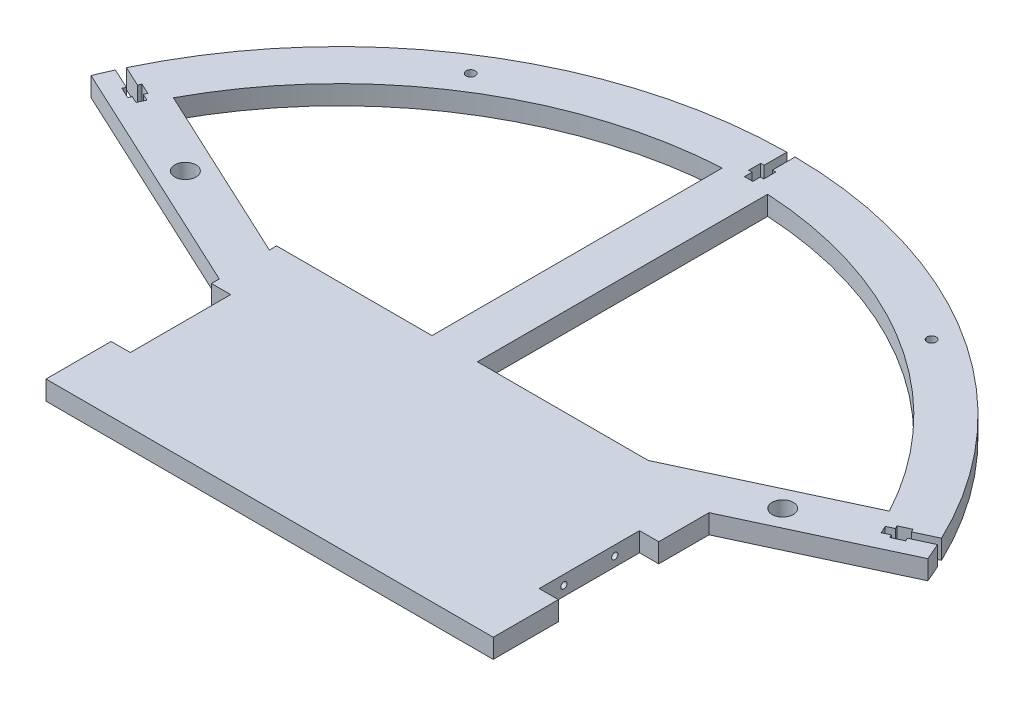
SolidWorks part; units mm, degrees
material "6061 Alloy"
ref_plane "Front Plane" through (0, 0, 0) normal (0, 0, 1) x (1, 0, 0)
ref_plane "Top Plane" through (0, 0, 0) normal (0, 1, 0) x (1, 0, 0)
ref_plane "Right Plane" through (0, 0, 0) normal (1, 0, 0) x (0, 0, -1)
sketch "Sketch1" plane through (0, 0, 0) normal (0, 1, 0) x (1, 0, 0)
  line L0 (0, 0) -> (0, 149.238) construction
  line L1 (0, 0) -> (135.2556, 63.0707) construction
  line L2 (0, 0) -> (-135.2556, 63.0707) construction
  line L3 (3.1696, 6.7973) -> (-132.0859, 69.868)
  line L4 (7.5, 0) -> (7.5, 149.238)
  line L5 (3.1696, -6.7973) -> (138.4252, 56.2734)
  line L6 (-3.1696, -6.7973) -> (-138.4252, 56.2734)
  line L7 (-7.5, 0) -> (-7.5, 149.238)
  line L8 (-3.1696, 6.7973) -> (132.0859, 69.868)
  line L10 (-58.85, -38.1) -> (88.95, -38.1)
  line L11 (-58.85, -38.1) -> (-58.85, 38.1)
  line L12 (-58.85, 38.1) -> (88.95, 38.1)
  line L13 (88.95, -38.1) -> (88.95, 38.1)
  line L14 (-58.85, -38.1) -> (88.95, 38.1) construction
  line L15 (-58.85, 38.1) -> (88.95, -38.1) construction
  circle A0 centre (0, 0) radius 150 construction
  circle A1 centre (0, 0) radius 149.238
  circle A2 centre (0, 0) radius 134.238
  circle A3 centre (0, 0) radius 14
  point P7 (0, 0)
  point P11 (0, 0)
  dimension "D1" = 150
  dimension "D2" = 0.762
  dimension "D3" = 15
  dimension "D10" = 28
  dimension "D4" = 65
  dimension "D5" = 65
  dimension "D8" = 147.8
  dimension "D9" = 76.2
  dimension "D11" = 58.85
  dimension "D12" = 38.1
  dimension "D6" = 7.5
  dimension "D7" = 7.5
extrude "Boss-Extrude1" add sketch "Sketch1" along normal mid plane 6.35
sketch "Sketch2" plane through (0, 0, 0) normal (0, 1, 0) x (1, 0, 0)
  line L0 (-1.375, 135.238) -> (-1.375, 149.238)
  line L1 (-1.375, 135.238) -> (1.375, 135.238)
  line L2 (-1.375, 149.238) -> (1.375, 149.238)
  line L3 (1.375, 135.238) -> (1.375, 149.238)
  line L4 (-1.375, 135.238) -> (1.375, 149.238) construction
  line L5 (-1.375, 149.238) -> (1.375, 135.238) construction
  line L6 (-2.5, 137.738) -> (-2.5, 141.738)
  line L7 (-2.5, 137.738) -> (2.5, 137.738)
  line L8 (-2.5, 141.738) -> (2.5, 141.738)
  line L9 (2.5, 137.738) -> (2.5, 141.738)
  line L10 (-2.5, 137.738) -> (2.5, 141.738) construction
  line L11 (-2.5, 141.738) -> (2.5, 137.738) construction
  line L12 (0, -1000) -> (0, 49000) construction
  line L13 (-1000, 0) -> (49000, 0) construction
  arc A1 (138.2543, 56.1937) -> (-138.2543, 56.1937) centre (0, 0) ccw construction
  point P1 (0, 142.238)
  point P2 (0, 139.738)
  dimension "D1" = 2.75
  dimension "D2" = 14
  dimension "D3" = 4
  dimension "D4" = 5
  dimension "D5" = 2.5
extrude "Cut-Extrude1" cut sketch "Sketch2" against normal through all both and the other way through all contours L7 L0 L1 L3 | L8 L0 L7 L3 | L7 L9 L8 L3 | L0 L8 L3 L2 | L8 L6 L7 L0
pattern_circular "CirPattern1" count 2 every 65 about axis through (0, 0, 0) along (0, 1, 0) of "Cut-Extrude1"
hole_wizard "Ø3.0 (3) Diameter Hole1" positions "Sketch3" profile "Sketch4" hole size "Ø3.0" standard "ANSI Metric" end condition up to next
sketch "Sketch3" plane through (0, 3.175, 0) normal (0, 1, 0) x (1, 0, 0)
  line L11 (0, 0) -> (-80.1855, 125.8661) construction
  line L13 (0, 0) -> (80.1855, 125.8661) construction
  line L16 (-48.85, -28.1) -> (78.95, -28.1)
  line L17 (-48.85, -28.1) -> (-48.85, 28.1)
  line L18 (-48.85, 28.1) -> (78.95, 28.1)
  line L19 (78.95, -28.1) -> (78.95, 28.1)
  line L20 (-48.85, -28.1) -> (78.95, 28.1) construction
  line L21 (-48.85, 28.1) -> (78.95, -28.1) construction
  line L24 (80.1855, 125.8661) -> (72.126, 113.2152)
  line L26 (-80.1855, 125.8661) -> (-72.126, 113.2152)
  line L32 (88.95, -38.1) -> (88.95, 33.2027) construction
  line L33 (-58.85, -38.1) -> (88.95, -38.1) construction
  line L34 (-58.85, -38.1) -> (-58.85, 19.1669) construction
  line L35 (-58.85, 38.1) -> (-7.5, 38.1) construction
  arc A14 (-1.375, 149.2317) -> (-134.6687, 64.3142) centre (0, 0) ccw construction
  arc A15 (-7.5, 134.0283) -> (-118.3013, 63.4401) centre (0, 0) ccw construction
  arc A16 (134.6687, 64.3142) -> (1.375, 149.2317) centre (0, 0) ccw construction
  arc A17 (118.3013, 63.4401) -> (7.5, 134.0283) centre (0, 0) ccw construction
  point P605 (-76.1558, 119.5406)
  point P607 (76.1558, 119.5406)
  dimension "D1" = 10
  dimension "D2" = 10
  dimension "D3" = 10
  dimension "D4" = 10
sketch "Sketch4" plane through (76.1558, 3.175, -119.5406) normal (1, 0, 0) x (0, 0, 1)
  line L0 (0, 0) -> (0, 6.35)
  line L1 (0, 6.35) -> (1.5, 6.35)
  line L2 (1.5, 6.35) -> (1.5, 0)
  line L5 (1.5, 0) -> (0, 0)
  line L11 (0, -6.35) -> (0, 107.95) construction
  dimension "Thru Hole Dia." = 3
  dimension "Thru Hole Depth" = 6.35
hole_wizard "Ø8.0 (8) Diameter Hole1" positions "Sketch5" profile "Sketch6" hole size "Ø8.0" standard "ANSI Metric"
sketch "Sketch5" plane through (0, 3.175, 0) normal (0, 1, 0) x (1, 0, 0)
  point P0 (0, 0)
sketch "Sketch6" plane through (0, 3.175, 0) normal (1, 0, 0) x (0, 0, 1)
  line L0 (0, 0) -> (0, 6.35)
  line L1 (0, 6.35) -> (4, 6.35)
  line L2 (4, 6.35) -> (4, 0)
  line L5 (4, 0) -> (0, 0)
  line L11 (0, -6.35) -> (0, 107.95) construction
  dimension "Thru Hole Dia." = 8
  dimension "Thru Hole Depth" = 6.35
sketch "Sketch8" plane through (0, 3.175, 0) normal (0, 1, 0) x (1, 0, 0)
  line L0 (-47.6, 30) -> (-47.6, -30) construction
  line L1 (-47.6, -30) -> (-53.95, -30) construction
  line L2 (-53.95, -30) -> (-53.95, 30) construction
  line L3 (-53.95, 30) -> (-47.6, 30) construction
  line L4 (79.85, 30) -> (79.85, -30) construction
  line L6 (73.5, -30) -> (73.5, 30) construction
  line L8 (-47.6, 30) -> (-47.6, -30)
  line L9 (-47.6, -30) -> (-53.95, -30)
  line L10 (-53.95, -30) -> (-53.95, 30)
  line L11 (-53.95, 30) -> (-47.6, 30)
  line L12 (79.85, 30) -> (79.85, -30)
  line L13 (79.85, -30) -> (73.5, -30)
  line L14 (73.5, -30) -> (73.5, 30)
  line L15 (73.5, 30) -> (79.85, 30)
  circle A1 centre (76.675, 20) radius 1.7272
  circle A2 centre (76.675, 20) radius 1.7272
  circle A3 centre (76.675, -20) radius 1.7272
  circle A4 centre (76.675, -20) radius 1.7272
  circle A5 centre (76.675, -10) radius 2.3813
  circle A6 centre (76.675, -10) radius 2.3813
  circle A7 centre (76.675, 10) radius 2.3813
  circle A8 centre (76.675, 10) radius 2.3813
  circle A13 centre (-50.775, -20) radius 1.7272
  circle A15 centre (-50.775, -20) radius 1.7272
  circle A64 centre (-50.775, 20) radius 1.7272
  circle A65 centre (-50.775, 20) radius 1.7272
  circle A66 centre (-50.775, -10) radius 2.3812
  circle A67 centre (-50.775, -10) radius 2.3812
  circle A68 centre (-50.775, 10) radius 2.3812
  circle A69 centre (-50.775, 10) radius 2.3812
  dimension "D1" = 0
  dimension "D2" = 0
  dimension "D3" = 0
  dimension "D4" = 0
  dimension "D5" = 0
  dimension "D6" = 0
  dimension "D7" = 0
  dimension "D8" = 0
hole_wizard "#8 Clearance Hole1" positions "Sketch9" profile "Sketch10" hole size "#8" standard "ANSI Inch"
sketch "Sketch9" plane through (0, 3.175, 0) normal (0, 1, 0) x (1, 0, 0)
  point P0 (-50.775, -20)
  point P3 (-50.775, 20)
  point P6 (76.675, -20)
  point P9 (76.675, 20)
sketch "Sketch10" plane through (-50.775, 3.175, 20) normal (1, 0, 0) x (0, 0, 1)
  line L0 (0, 0) -> (0, 14.1807)
  line L1 (0, 14.1807) -> (2.2479, 12.83)
  line L2 (2.2479, 12.83) -> (2.2479, 0)
  line L5 (2.2479, 0) -> (0, 0)
  line L10 (0, 14.1807) -> (-2.2479, 12.83) construction
  line L11 (0, -6.35) -> (0, 107.95) construction
  dimension "Hole Dia." = 4.4958
  dimension "Hole Depth" = 12.83
  dimension "Drill Angle" = 118
hole_wizard "3/16 (0.1875) Dowel Hole1" positions "Sketch11" profile "Sketch12" hole size "3/16" standard "ANSI Inch"
sketch "Sketch11" plane through (0, 3.175, 0) normal (0, 1, 0) x (1, 0, 0)
  point P0 (-50.775, -10)
  point P3 (-50.775, 10)
  point P6 (76.675, -10)
  point P9 (76.675, 10)
sketch "Sketch12" plane through (-50.775, 3.175, 10) normal (1, 0, 0) x (0, 0, 1)
  line L0 (0, 0) -> (0, 14.2608)
  line L1 (0, 14.2608) -> (2.3812, 12.83)
  line L2 (2.3812, 12.83) -> (2.3812, 0)
  line L5 (2.3812, 0) -> (0, 0)
  line L10 (0, 14.2608) -> (-2.3813, 12.83) construction
  line L11 (0, -6.35) -> (0, 107.95) construction
  dimension "Hole Dia." = 4.7625
  dimension "Hole Depth" = 12.83
  dimension "Drill Angle" = 118
sketch "Sketch13" plane through (0, 3.175, 0) normal (0, 1, 0) x (1, 0, 0)
  line L0 (-58.85, -16.58) -> (-52.5, -16.58)
  line L1 (-58.85, -16.58) -> (-58.85, 16.58)
  line L2 (-52.5, -16.58) -> (-52.5, 16.58)
  line L3 (-58.85, 16.58) -> (-52.5, 16.58)
  line L4 (-58.85, -38.1) -> (-58.85, 19.1669) construction
  line L5 (88.95, -16.58) -> (82.6, -16.58)
  line L6 (88.95, -16.58) -> (88.95, 16.58)
  line L7 (82.6, -16.58) -> (82.6, 16.58)
  line L8 (88.95, 16.58) -> (82.6, 16.58)
  line L9 (88.95, -38.1) -> (88.95, 33.2027) construction
  point P6 (-52.5, 0)
  point P14 (82.6, 0)
  dimension "D1" = 6.35
  dimension "D2" = 33.16
  dimension "D3" = 33.16
  dimension "D4" = 6.35
extrude "Cut-Extrude2" cut sketch "Sketch13" against normal through all
hole_wizard "M2.5x0.45 Tapped Hole1" positions "Sketch14" profile "Sketch15" tap size "M2.5x0.45" standard "ANSI Metric"
sketch "Sketch14" plane through (-52.5, 0, 0) normal (-1, 0, 0) x (0, 0, 1)
  point P0 (-8.415, 0)
  point P2 (8.415, 0)
  dimension "D1" = 8.415
  dimension "D2" = 8.415
cosmetic thread "Hole Thread1" parameters "D1"=5, "D2"=2.5
cosmetic thread "Hole Thread2" parameters "D1"=5, "D2"=2.5
sketch "Sketch15" plane through (-52.5, 0, -8.415) normal (0, 1, 0) x (0, 0, 1)
  line L0 (0, 0) -> (0, 6.9659)
  line L1 (0, 6.9659) -> (1.025, 6.35)
  line L2 (1.025, 6.35) -> (1.025, 0)
  line L5 (1.025, 0) -> (0, 0)
  line L10 (0, 6.9659) -> (-1.025, 6.35) construction
  line L11 (0, -6.35) -> (0, 107.95) construction
  dimension "Tap Drill Dia." = 2.05
  dimension "Tap Drill Depth" = 6.35
  dimension "Drill Angle" = 118
ref_plane "Plane1" through (15.05, 0, 0) normal (-1, 0, 0) x (0, 0, 1)
mirror "Mirror1" about plane through (15.05, 0, 0) normal (-1, 0, 0) of "M2.5x0.45 Tapped Hole1"
cosmetic thread "Hole Thread3" parameters "D1"=5, "D2"=2.5
cosmetic thread "Hole Thread4" parameters "D1"=5, "D2"=2.5
hole_wizard "M6 Clearance Hole1" positions "Sketch18" profile "Sketch17" hole size "M6" standard "ANSI Metric" end condition up to next
sketch "Sketch18" plane through (0, 3.175, 0) normal (0, 1, 0) x (1, 0, 0)
  line L0 (-122.5673, 57.154) -> (0, 0)
  line L1 (-123.1484, 55.9079) -> (-121.9862, 58.4002) construction
  line L2 (0, 0) -> (122.5673, 57.154)
  line L3 (121.9862, 58.4002) -> (123.1484, 55.9079) construction
  point P14 (-95.378, 44.4755)
  point P16 (99.9096, 46.5886)
  dimension "D1" = 30
  dimension "D2" = 25
sketch "Sketch17" plane through (99.9096, 3.175, -46.5886) normal (1, 0, 0) x (0, 0, 1)
  line L0 (0, 0) -> (0, 6.35)
  line L1 (0, 6.35) -> (3.5, 6.35)
  line L2 (3.5, 6.35) -> (3.5, 0)
  line L5 (3.5, 0) -> (0, 0)
  line L11 (0, -6.35) -> (0, 107.95) construction
  dimension "Thru Hole Dia." = 7
  dimension "Thru Hole Depth" = 6.35
